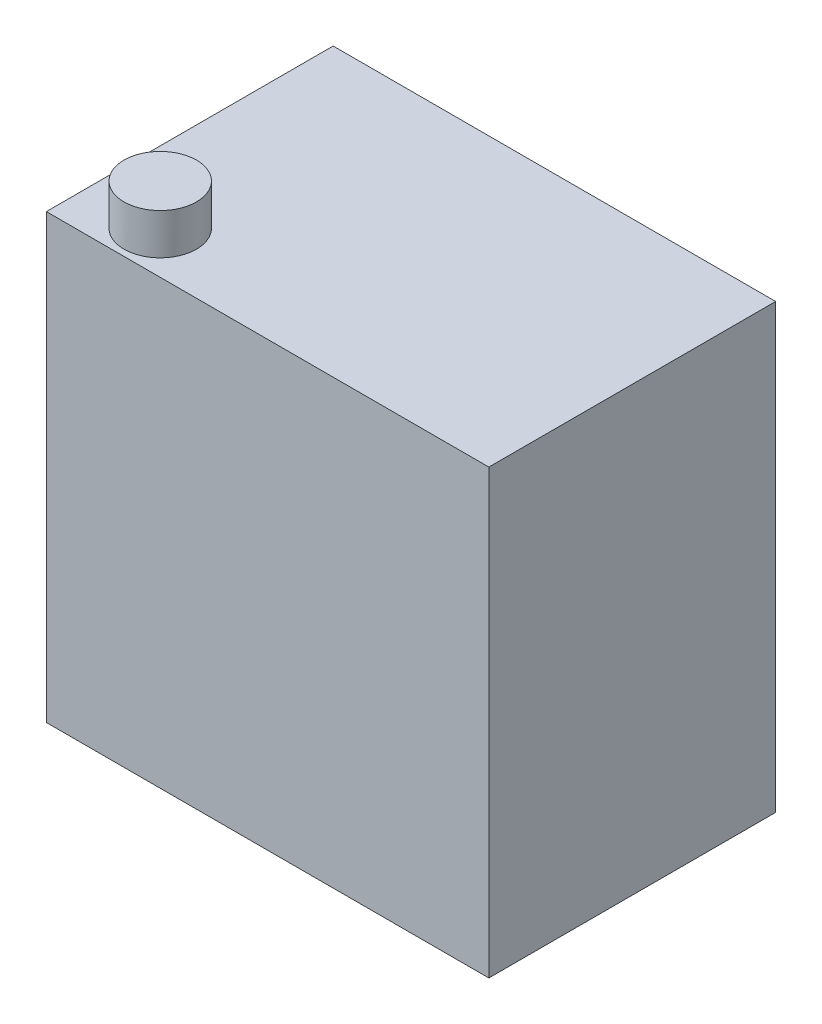
SolidWorks part; units mm, degrees
material "1060 合金"
ref_plane "前视基准面" through (0, 0, 0) normal (0, 0, 1) x (1, 0, 0)
ref_plane "上视基准面" through (0, 0, 0) normal (0, 1, 0) x (1, 0, 0)
ref_plane "右视基准面" through (0, 0, 0) normal (1, 0, 0) x (0, 0, -1)
sketch "草图1" plane through (0, 0, 0) normal (0, 0, 1) x (1, 0, 0)
  line L1 (0, 0) -> (108, 0)
  line L2 (0, 0) -> (0, 108)
  line L3 (0, 108) -> (108, 108)
  line L4 (108, 0) -> (108, 108)
  dimension "D1" = 108
  dimension "D2" = 108
extrude "拉伸1" add sketch "草图1" along normal blind 70
sketch "草图2" plane through (0, 108, 0) normal (0, 1, 0) x (-1, 0, 0)
  circle A0 centre (-17.4293, 59.6355) radius 8.8445
extrude "拉伸2" add sketch "草图2" along normal blind 10
